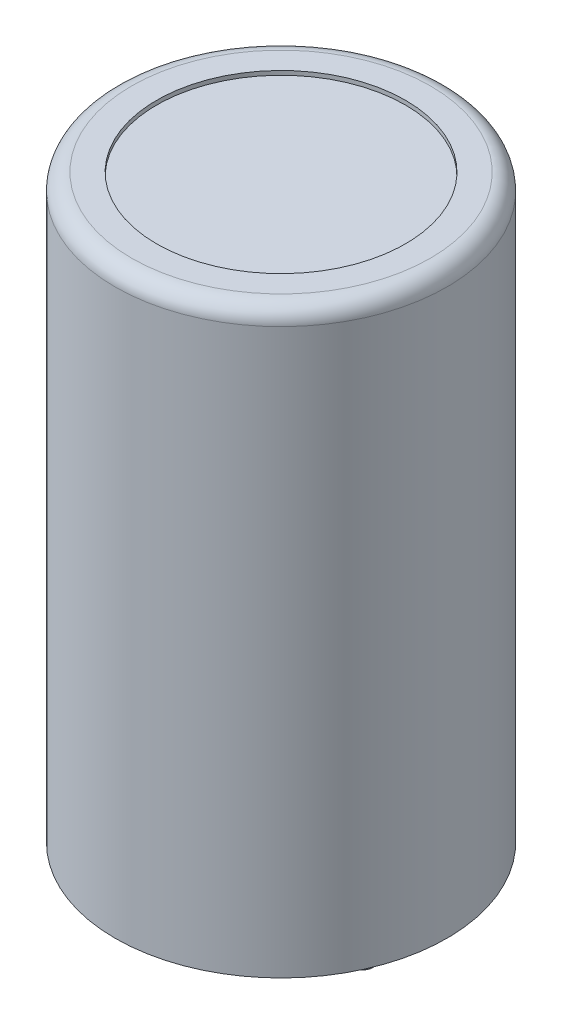
SolidWorks part; units mm, degrees
ref_plane "Front Plane" through (0, 0, 0) normal (0, 0, 1) x (1, 0, 0)
ref_plane "Top Plane" through (0, 0, 0) normal (0, 1, 0) x (1, 0, 0)
ref_plane "Right Plane" through (0, 0, 0) normal (1, 0, 0) x (0, 0, -1)
sketch "Sketch1" plane through (0, 0, 0) normal (0, 1, 0) x (1, 0, 0)
  circle A0 centre (0, 0) radius 5.08
  dimension "D1" = 10.16
extrude "Boss-Extrude1" add sketch "Sketch1" along normal blind 17.78
sketch "Sketch2" plane through (0, 0, 0) normal (0, -1, 0) x (1, 0, 0)
  line L0 (-2.5, 0) -> (2.5, 0) construction
  circle A0 centre (-2.5, 0) radius 0.3175
  circle A1 centre (2.5, 0) radius 0.3175
  dimension "D2" = 0.635
  dimension "D1" = 5
extrude "Boss-Extrude2" add sketch "Sketch2" along normal blind 1.905
sketch "Sketch3" plane through (0, 17.78, 0) normal (0, 1, 0) x (1, 0, 0)
  circle A0 centre (0, 0) radius 3.81
  circle A1 centre (0, 0) radius 5.08 construction
  dimension "D1" = 1.27
extrude "Cut-Extrude1" cut sketch "Sketch3" against normal blind 0.127
fillet "Fillet1" radius 0.508 1 edges at (0, 17.78, 5.08)
